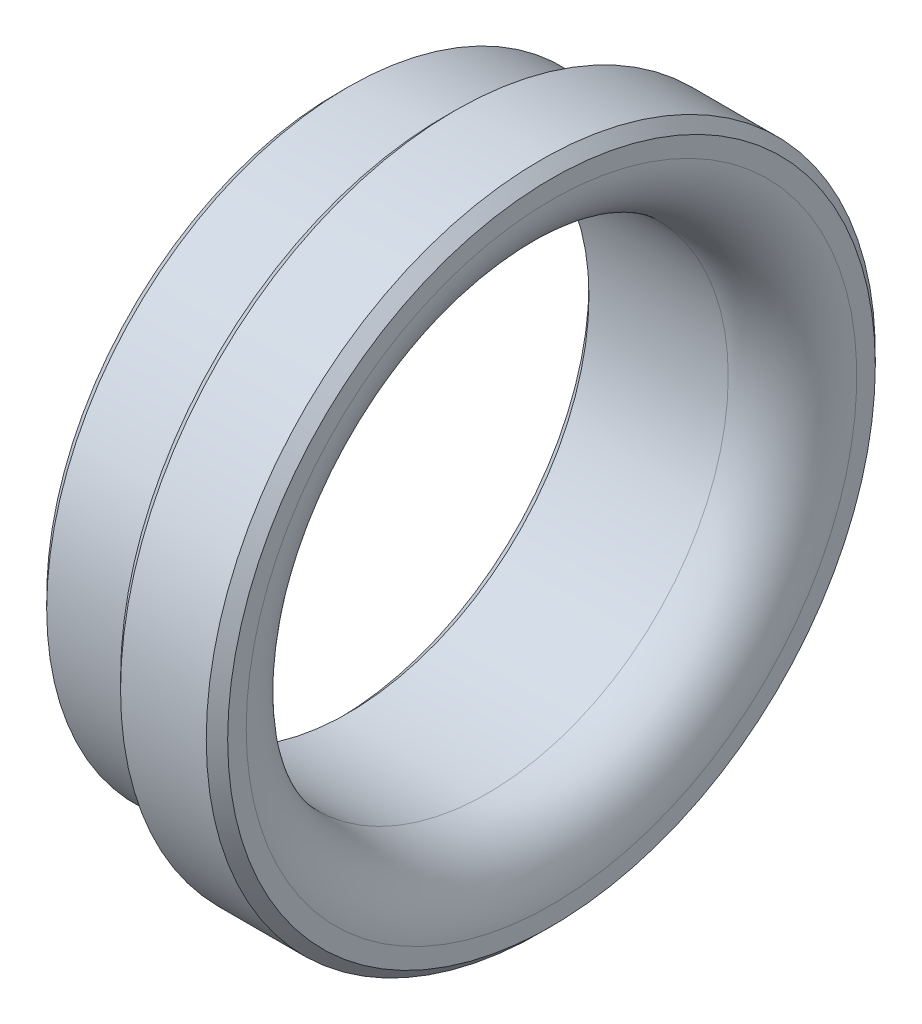
SolidWorks part; units mm, degrees
material "6061-T6 (SS)"
ref_plane "Front Plane" through (0, 0, 0) normal (0, 0, 1) x (1, 0, 0)
ref_plane "Top Plane" through (0, 0, 0) normal (0, 1, 0) x (1, 0, 0)
ref_plane "Right Plane" through (0, 0, 0) normal (1, 0, 0) x (0, 0, -1)
ref_axis "Axis1" through (-88.99, 0, 0) along (1, 0, 0)
sketch "Sketch1" plane through (0, 0, 0) normal (0, 0, 1) x (1, 0, 0)
  line L0 (0, 0) -> (25.4, 0) construction
  line L1 (-88.99, 0) -> (88.99, 0) construction
  line L2 (0, -28.575) -> (0, 28.575) construction
  line L3 (0, 28.575) -> (0, 35.7188)
  line L4 (0, 35.7188) -> (12.7, 35.7188)
  line L5 (25.4, -39.6621) -> (25.4, -28.575) construction
  line L6 (25.4, 28.575) -> (25.4, -28.575) construction
  line L7 (0, 28.575) -> (25.4, 28.575)
  line L8 (12.7, -35.7188) -> (12.7, -39.6621) construction
  line L9 (12.7, -39.6621) -> (25.4, -39.6621) construction
  line L10 (0, -35.7188) -> (12.7, -35.7188) construction
  line L11 (0, -28.575) -> (0, -35.7188) construction
  line L12 (12.7, 35.7188) -> (12.7, 39.6621)
  line L13 (12.7, 39.6621) -> (25.4, 39.6621)
  line L14 (25.4, 39.6621) -> (25.4, 28.575)
  dimension "D1" = 71.4375
  dimension "D2" = 57.15
  dimension "D3" = 25.4
  dimension "D4" = 79.3242
  dimension "D5" = 12.7
revolve "Revolve1" add sketch "Sketch1" angle 360 about axis through (-88.99, 0, 0) along (1, 0, 0)
chamfer "Chamfer1" distance 1.27 angle 45 4 edges at (25.4, 0, 39.6621) (12.7, 0, 39.6621) (0, 0, 28.575) (0, 0, 35.7188)
fillet "Fillet1" radius 7.62 1 edges at (25.4, 0, 28.575)
